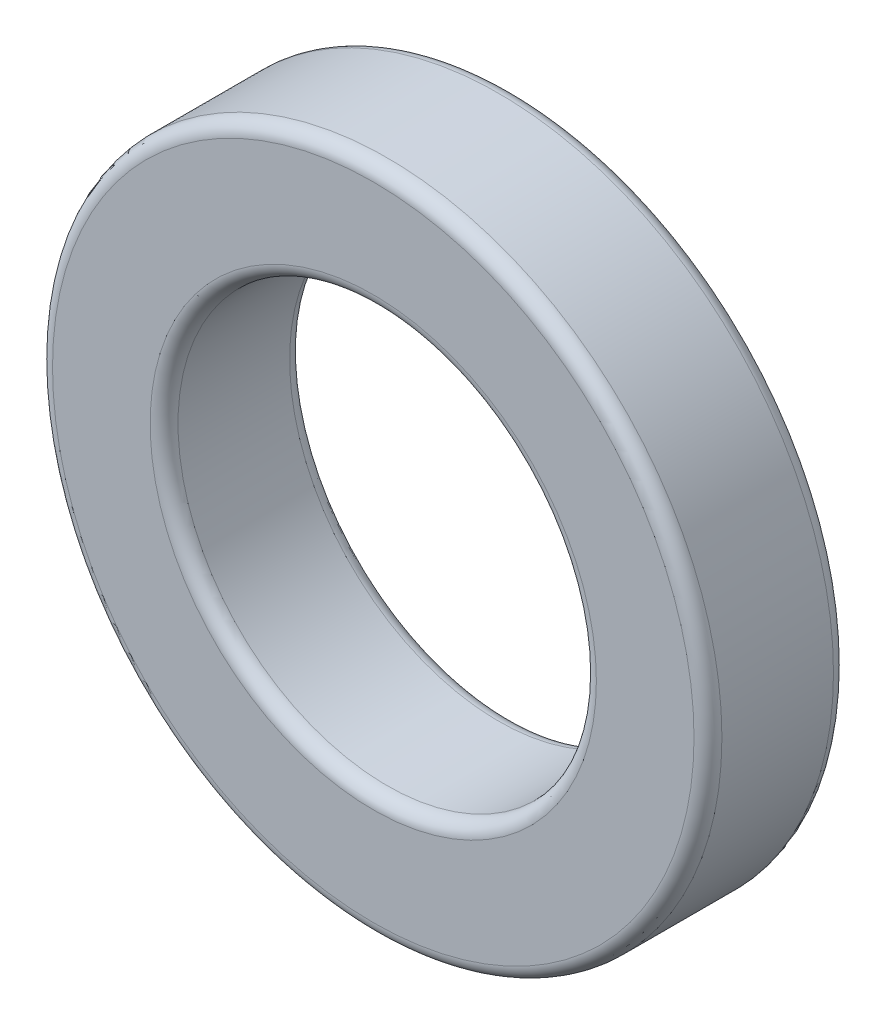
SolidWorks part; units mm, degrees
ref_plane "前视基准面" through (0, 0, 0) normal (0, 0, 1) x (1, 0, 0)
ref_plane "上视基准面" through (0, 0, 0) normal (0, 1, 0) x (1, 0, 0)
ref_plane "右视基准面" through (0, 0, 0) normal (1, 0, 0) x (0, 0, -1)
sketch "草图1" plane through (0, 0, 0) normal (0, 0, 1) x (1, 0, 0)
  circle A0 centre (0, 0) radius 12
  circle A1 centre (0, 0) radius 7.5
  dimension "D1" = 15
  dimension "D2" = 24
extrude "凸台-拉伸1" add sketch "草图1" along normal blind 5
fillet "圆角1" radius 0.5 4 edges at (7.5, 0, 0) (7.5, 0, 5) (12, 0, 0) (12, 0, 5)
